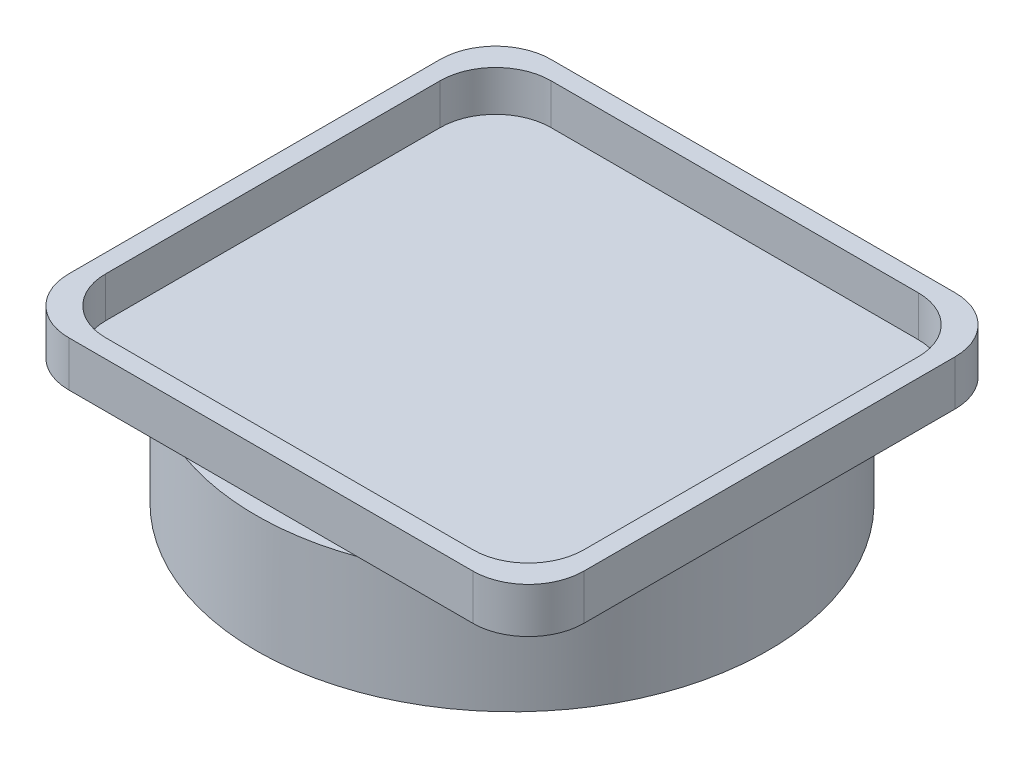
SolidWorks part; units mm, degrees
ref_plane "Ön Düzlem" through (0, 0, 0) normal (0, 0, 1) x (1, 0, 0)
ref_plane "Üst Düzlem" through (0, 0, 0) normal (0, 1, 0) x (1, 0, 0)
ref_plane "Sağ Düzlem" through (0, 0, 0) normal (1, 0, 0) x (0, 0, -1)
sketch "Çizim1" plane through (0, 0, 0) normal (0, 1, 0) x (1, 0, 0)
  line L0 (-13.955, -13.065) -> (13.955, -13.065)
  line L1 (-12.955, -12.065) -> (12.955, -12.065)
  line L2 (-12.955, -12.065) -> (-12.955, 12.065)
  line L3 (-12.955, 12.065) -> (12.955, 12.065)
  line L4 (12.955, -12.065) -> (12.955, 12.065)
  line L5 (13.955, -13.065) -> (13.955, 13.065)
  line L6 (-13.955, 13.065) -> (13.955, 13.065)
  line L7 (-13.955, -13.065) -> (-13.955, 13.065)
  point P0 (0, 0)
  dimension "D1" = 24.13
  dimension "D2" = 25.91
  dimension "D3" = 1
extrude "Yükseklik-Ekstrüzyon1" add sketch "Çizim1" along normal blind 2.2
fillet "Radyus1" radius 3 8 edges at (-12.955, 1.1, 12.065) (-13.955, 1.1, 13.065) (13.955, 1.1, 13.065) (12.955, 1.1, 12.065) (12.955, 1.1, -12.065) (13.955, 1.1, -13.065) (-13.955, 1.1, -13.065) (-12.955, 1.1, -12.065)
sketch "Çizim2" plane through (0, 0, 0) normal (0, -1, 0) x (1, 0, 0)
  line L4 (10.955, 13.065) -> (-10.955, 13.065)
  line L5 (-13.955, 10.065) -> (-13.955, -10.065)
  line L6 (-10.955, -13.065) -> (10.955, -13.065)
  line L7 (13.955, -10.065) -> (13.955, 10.065)
  line L8 (10.955, 13.065) -> (-10.955, 13.065)
  line L9 (-13.955, 10.065) -> (-13.955, -10.065)
  line L10 (-10.955, -13.065) -> (10.955, -13.065)
  line L11 (13.955, -10.065) -> (13.955, 10.065)
  arc A4 (-10.955, 13.065) -> (-13.955, 10.065) centre (-10.955, 10.065) ccw
  arc A5 (-13.955, -10.065) -> (-10.955, -13.065) centre (-10.955, -10.065) ccw
  arc A6 (10.955, -13.065) -> (13.955, -10.065) centre (10.955, -10.065) ccw
  arc A7 (13.955, 10.065) -> (10.955, 13.065) centre (10.955, 10.065) ccw
  arc A8 (-10.955, 13.065) -> (-13.955, 10.065) centre (-10.955, 10.065) ccw
  arc A9 (-13.955, -10.065) -> (-10.955, -13.065) centre (-10.955, -10.065) ccw
  arc A10 (10.955, -13.065) -> (13.955, -10.065) centre (10.955, -10.065) ccw
  arc A11 (13.955, 10.065) -> (10.955, 13.065) centre (10.955, 10.065) ccw
  dimension "D1" = 0
extrude "Yükseklik-Ekstrüzyon2" add sketch "Çizim2" along normal blind 0.252
sketch "Çizim3" plane through (0, -0.252, 0) normal (0, -1, 0) x (1, 0, 0)
  circle A0 centre (0, 0) radius 13.875
  dimension "D1" = 27.75
extrude "Yükseklik-Ekstrüzyon3" add sketch "Çizim3" along normal blind 6.35
